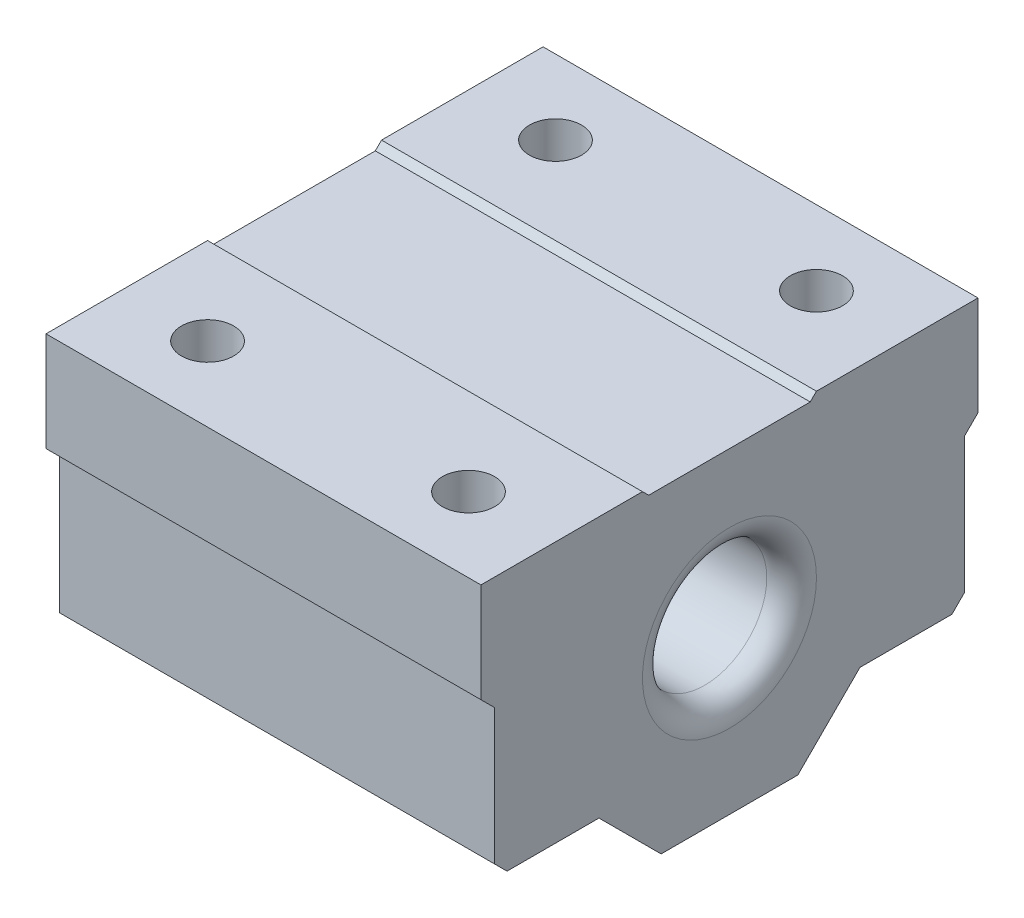
SolidWorks part; units mm, degrees
material "1060 Alloy"
ref_plane "Front Plane" through (0, 0, 0) normal (0, 0, 1) x (1, 0, 0)
ref_plane "Top Plane" through (0, 0, 0) normal (0, 1, 0) x (1, 0, 0)
ref_plane "Right Plane" through (0, 0, 0) normal (1, 0, 0) x (0, 0, -1)
sketch "Sketch1" plane through (0, 0, 0) normal (1, 0, 0) x (0, 0, -1)
  line L0 (0, 18) -> (1.1, 16.9)
  line L1 (14.5, 0) -> (25.5, 0)
  line L2 (0, 18) -> (0, 26)
  line L3 (37.9, 5) -> (30.5, 5)
  line L4 (38.9, 16.9) -> (38.9, 6)
  line L5 (9.5, 5) -> (14.5, 0)
  line L6 (1.1, 16.9) -> (1.1, 6)
  line L7 (2.1, 5) -> (9.5, 5)
  line L8 (20, 13) -> (20, -4.9054) construction
  line L9 (30.5, 5) -> (25.5, 0)
  line L10 (40, 18) -> (40, 26)
  line L11 (40, 18) -> (38.9, 16.9)
  line L12 (0, 26) -> (13, 26)
  line L13 (13, 26) -> (13.5, 25.5)
  line L14 (13.5, 25.5) -> (20, 25.5)
  line L15 (26.5, 25.5) -> (20, 25.5)
  line L16 (27, 26) -> (26.5, 25.5)
  line L17 (27, 26) -> (40, 26)
  line L18 (1.1, 6) -> (2.1, 5)
  line L19 (38.9, 6) -> (37.9, 5)
  circle A0 centre (20, 13) radius 5
  point P1 (38.9, 5)
  point P13 (1.1, 5)
  point P18 (20, 0)
  dimension "D3" = 21
  dimension "D4" = 10
  dimension "D2" = 40
  dimension "D5" = 8
  dimension "D6" = 13
  dimension "D7" = 135
  dimension "D8" = 1.1
  dimension "D9" = 135
  dimension "D10" = 5.5
  dimension "D11" = 26
  dimension "D12" = 135
  dimension "D13" = 0.5
  dimension "D14" = 13
extrude "Boss-Extrude1" add sketch "Sketch1" along normal blind 35
sketch "Sketch2" plane through (0, 26, 0) normal (0, 1, 0) x (1, 0, 0)
  line L0 (0, 0) -> (35, 40) construction
  line L1 (35, 40) -> (0, 40) construction
  line L2 (0, 40) -> (35, 0) construction
  line L4 (28, 6) -> (7, 6) construction
  line L5 (28, 6) -> (28, 34) construction
  line L6 (28, 34) -> (7, 34) construction
  line L7 (7, 6) -> (7, 34) construction
  line L8 (28, 6) -> (7, 34) construction
  line L9 (28, 34) -> (7, 6) construction
  point P2 (17.5, 20)
  point P13 (-13.6988, 29.5376)
  point P14 (7, 34)
  point P15 (28, 34)
  point P16 (28, 6)
  point P17 (7, 6)
  dimension "D1" = 21
  dimension "D2" = 28
hole_wizard "M5 Tapped Hole1" positions "3DSketch1" profile "Sketch3" tap size "M5" standard "ISO"
sketch3d "3DSketch1"
  point P0 (7, 26, -34)
  point P3 (28, 26, -34)
  point P6 (28, 26, -6)
  point P9 (7, 26, -6)
sketch "Sketch3" plane through (7, 26, -34) normal (1, 0, 0) x (0, 0, 1)
  line L0 (0, 0) -> (0, 23.2618)
  line L1 (0, 23.2618) -> (2.1, 22)
  line L2 (2.1, 22) -> (2.1, 0)
  line L5 (2.1, 0) -> (0, 0)
  line L10 (0, 23.2618) -> (-2.1, 22) construction
  line L11 (0, -6.35) -> (0, 107.95) construction
  dimension "Tap Drill Dia." = 4.2
  dimension "Tap Drill Depth" = 22
  dimension "Drill Angle" = 118
cosmetic thread "Hole Thread1" parameters "D1"=12, "D2"=5
cosmetic thread "Hole Thread2" parameters "D1"=12, "D2"=5
cosmetic thread "Hole Thread3" parameters "D1"=12, "D2"=5
cosmetic thread "Hole Thread4" parameters "D1"=12, "D2"=5
chamfer "Chamfer1" distance 1 angle 45 4 edges at (7, 5, -3.9) (28, 5, -3.9) (28, 5, -31.9) (7, 5, -31.9)
fillet "Fillet1" radius 2 2 edges at (0, 13, -25) (35, 13, -25)
